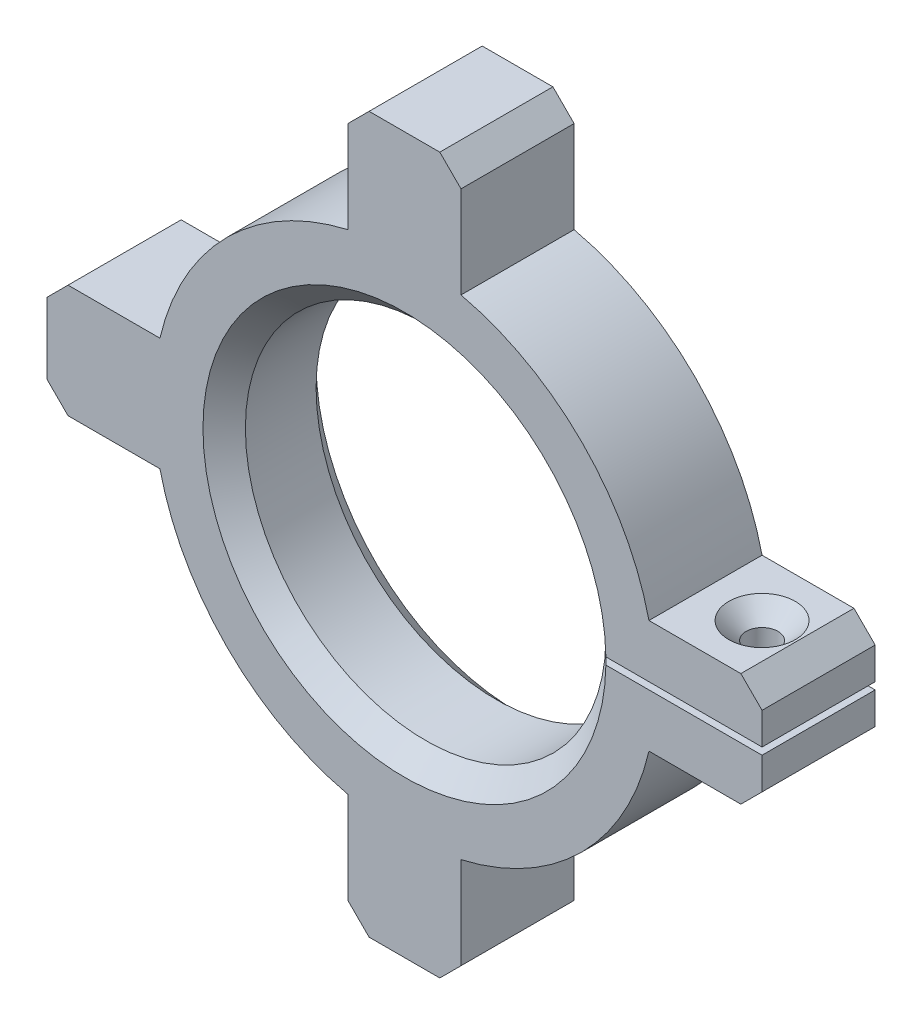
SolidWorks part; units mm, degrees
ref_plane "Спереди" through (0, 0, 0) normal (0, 0, 1) x (1, 0, 0)
ref_plane "Сверху" through (0, 0, 0) normal (0, 1, 0) x (1, 0, 0)
ref_plane "Справа" through (0, 0, 0) normal (1, 0, 0) x (0, 0, -1)
sketch "Эскиз1" plane through (0, 0, 0) normal (0, 0, 1) x (1, 0, 0)
  line L0 (-1267.9455, 0) -> (62129.3286, 0) construction
  line L3 (0, -1000) -> (0, 49000) construction
  line L4 (-8, 50.5868) -> (8, 50.5868)
  line L5 (8, 50.5868) -> (8, 34.5868)
  line L6 (-8, 50.5868) -> (-8, 34.5868)
  line L7 (50.5868, 8) -> (34.5868, 8) [skipped]
  line L8 (50.5868, 8) -> (50.5868, -8) [skipped]
  line L9 (50.5868, -8) -> (34.5868, -8) [skipped]
  line L10 (8, -50.5868) -> (8, -34.5868)
  line L11 (8, -50.5868) -> (-8, -50.5868)
  line L12 (-8, -50.5868) -> (-8, -34.5868)
  line L13 (-50.5868, -8) -> (-34.5868, -8)
  line L14 (-50.5868, -8) -> (-50.5868, 8)
  line L15 (-50.5868, 8) -> (-34.5868, 8)
  line L16 (50.5868, -8) -> (34.5868, -8)
  line L17 (50.5868, -8) -> (50.5868, -0.5)
  line L18 (50.5868, 8) -> (34.5868, 8)
  line L19 (50.5868, 0.5) -> (25.4951, 0.5)
  line L20 (50.5868, -0.5) -> (25.4951, -0.5)
  line L21 (50.5868, -0.5) -> (50.5868, 0) construction
  line L22 (50.5868, 0.5) -> (50.5868, 8)
  line L23 (50.5868, 0) -> (50.5868, 0.5) construction
  arc A4 (25.4951, 0.5) -> (25.4951, -0.5) centre (0, 0) ccw
  arc A5 (-34.5868, -8) -> (-8, -34.5868) centre (0, 0) ccw
  arc A6 (-35.5, 0) -> (-34.5868, -8) centre (0, 0) ccw construction
  arc A7 (-34.5868, 8) -> (-35.5, 0) centre (0, 0) ccw construction
  arc A8 (0, 35.5) -> (-8, 34.5868) centre (0, 0) ccw construction
  arc A9 (-8, 34.5868) -> (-34.5868, 8) centre (0, 0) ccw
  arc A10 (8, 34.5868) -> (0, 35.5) centre (0, 0) ccw construction
  arc A11 (35.4965, 0.5) -> (34.5868, 8) centre (0, 0) ccw construction
  arc A12 (34.5868, 8) -> (8, 34.5868) centre (0, 0) ccw
  arc A13 (34.5868, -8) -> (35.4965, -0.5) centre (0, 0) ccw construction
  arc A14 (35.4965, -0.5) -> (35.5, 0) centre (0, 0) ccw construction
  arc A15 (35.5, 0) -> (35.4965, 0.5) centre (0, 0) ccw construction
  arc A16 (25.4951, -0.5) -> (25.5, 0) centre (0, 0) ccw construction
  arc A17 (25.5, 0) -> (25.4951, 0.5) centre (0, 0) ccw construction
  arc A18 (0, -35.5) -> (8, -34.5868) centre (0, 0) ccw construction
  arc A19 (8, -34.5868) -> (34.5868, -8) centre (0, 0) ccw
  arc A20 (-8, -34.5868) -> (0, -35.5) centre (0, 0) ccw construction
  point P12 (0, 50.5868)
  point P28 (0, 0)
  point P39 (3.8188, 43.4988)
  point P41 (43.7817, 5)
  point P42 (43.8431, 8)
  dimension "D1" = 51
  dimension "D2" = 10
  dimension "D4" = 1
  dimension "D5" = 16
  dimension "D6" = 16
  dimension "D3" = 4
extrude "Бобышка-Вытянуть1" add sketch "Эскиз1" along normal mid plane 16
hole_wizard "Зенковка для винта с полупотайной головкой M41" positions "Трехмерный эскиз1" profile "Эскиз4" countersink size "M4" standard "DIN" end condition through all
sketch3d "Трехмерный эскиз1"
  line L0 (34.5868, 8, 8) -> (50.5868, 8, -8) construction
  point P0 (42.5868, 8, 0)
sketch "Эскиз4" plane through (42.5868, 8, 0) normal (1, 0, 0) x (0, 0, 1)
  line L0 (0, 0) -> (0, 58.5868)
  line L1 (0, 58.5868) -> (2.25, 58.5868)
  line L2 (2.25, 58.5868) -> (2.25, 2.45)
  line L3 (2.25, 2.45) -> (4.7, 0)
  line L5 (4.7, 0) -> (0, 0)
  line L6 (-2.25, 2.45) -> (-4.7, 0) construction
  line L11 (0, -6.35) -> (0, 107.95) construction
  dimension "Диаметр сквозного отверстия" = 4.5
  dimension "Глубина сквозного отверстия" = 58.5868
  dimension "Диаметр передней зенковки" = 9.4
  dimension "Угол передней зенковки" = 90
sketch "Эскиз5" plane through (0, -8, 0) normal (0, -1, 0) x (1, 0, 0)
  line L1 (46.917, 0) -> (44.7519, 3.75)
  line L2 (44.7519, 3.75) -> (40.4218, 3.75)
  line L3 (40.4218, 3.75) -> (38.2567, 0)
  line L4 (38.2567, 0) -> (40.4218, -3.75)
  line L5 (40.4218, -3.75) -> (44.7519, -3.75)
  line L6 (44.7519, -3.75) -> (46.917, 0)
  circle A0 centre (42.5868, 0) radius 2.25 construction
  circle A1 centre (42.5868, 0) radius 2.25 construction
  circle A2 centre (42.5868, 0) radius 3.75 construction
  dimension "D1" = 7.5
extrude "Вырез-Вытянуть2" cut sketch "Эскиз5" against normal blind 5
chamfer "Фаска1" distance 3 angle 45 10 edges at (50.5868, 8, 0) (50.5868, -8, 0) (8, -50.5868, 0) (-8, -50.5868, 0) (-50.5868, -8, 0) (-50.5868, 8, 0) (8, 50.5868, 0) (-8, 50.5868, 0) (-25.5, 0, 8) (-25.5, 0, -8)
